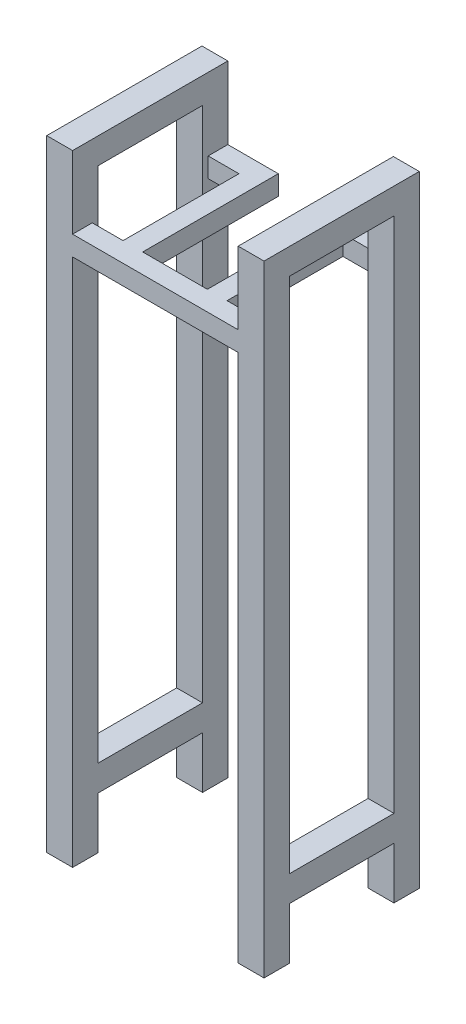
SolidWorks part; units mm, degrees
ref_plane "Front Plane" through (0, 0, 0) normal (0, 0, 1) x (1, 0, 0)
ref_plane "Top Plane" through (0, 0, 0) normal (0, 1, 0) x (1, 0, 0)
ref_plane "Right Plane" through (0, 0, 0) normal (1, 0, 0) x (0, 0, -1)
sketch "Sketch5" plane through (0, 0, 0) normal (0, 0, 1) x (1, 0, 0)
  line L0 (105, 600) -> (105, 0) construction
  line L1 (0, 0) -> (210, 0)
  line L2 (0, 0) -> (0, 600)
  line L3 (0, 600) -> (210, 600)
  line L4 (210, 0) -> (210, 600)
  line L6 (185, 575) -> (25, 575)
  line L7 (185, 575) -> (185, 0)
  line L8 (185, 0) -> (25, 0)
  line L9 (25, 575) -> (25, 0)
  line L10 (185, 575) -> (25, 0) construction
  line L11 (185, 0) -> (25, 575) construction
  point P7 (105, 287.5)
  dimension "D1" = 600
  dimension "D2" = 210
  dimension "D3" = 25
  dimension "D4" = 25
extrude "Boss-Extrude5" add sketch "Sketch5" along normal blind 150 contours L9 L6 L7 L1 L4 L3 L2
sketch "Sketch6" plane through (0, 0, 0) normal (-1, 0, 0) x (0, 0, 1)
  line L0 (75, 600) -> (75, 0) construction
  line L1 (150, 600) -> (0, 600) construction
  line L2 (150, 0) -> (0, 0) construction
  line L4 (125.5453, 50) -> (24.4547, 50)
  line L5 (125.5453, 50) -> (125.5453, 0)
  line L6 (125.5453, 0) -> (24.4547, 0)
  line L7 (24.4547, 50) -> (24.4547, 0)
  line L8 (125.5453, 50) -> (24.4547, 0) construction
  line L9 (125.5453, 0) -> (24.4547, 50) construction
  line L10 (125.5453, 75) -> (24.4547, 75)
  line L11 (125.5453, 75) -> (125.5453, 575)
  line L12 (125.5453, 575) -> (24.4547, 575)
  line L13 (24.4547, 75) -> (24.4547, 575)
  line L14 (125.5453, 75) -> (24.4547, 575) construction
  line L15 (125.5453, 575) -> (24.4547, 75) construction
  point P6 (75, 25)
  point P11 (75, 325)
  point P17 (0, 0)
  dimension "D1" = 25
  dimension "D3" = 25
  dimension "D4" = 50
extrude "Cut-Extrude1" cut sketch "Sketch6" against normal through all
sketch "Sketch7" plane through (0, 600, 0) normal (0, 1, 0) x (1, 0, 0)
  line L0 (105, -150) -> (105, 0) construction
  line L1 (0, -150) -> (210, -150) construction
  line L2 (0, 0) -> (210, 0) construction
  line L3 (210, -150) -> (210, 0) construction
  line L4 (25, -150) -> (185, -150)
  line L5 (25, -150) -> (25, 0)
  line L6 (25, 0) -> (185, 0)
  line L7 (185, -150) -> (185, 0)
  line L8 (25, -150) -> (185, 0) construction
  line L9 (25, 0) -> (185, -150) construction
  point P6 (105, -75)
  dimension "D1" = 0
  dimension "D2" = 25
extrude "Cut-Extrude2" cut sketch "Sketch7" against normal up to next
sketch "Sketch8" plane through (0, 0, 0) normal (0, 0, -1) x (-1, 0, 0)
  line L0 (-185, 600) -> (-185, 0) construction
  line L1 (-185, 530) -> (-25, 530)
  line L2 (-185, 530) -> (-185, 511)
  line L3 (-185, 511) -> (-25, 511)
  line L4 (-25, 530) -> (-25, 511)
  line L5 (-25, 600) -> (-25, 0) construction
  line L7 (-105, 530) -> (-105, 511) construction
  line L8 (0, 600) -> (-25, 600) construction
  line L9 (-73.75, 511) -> (-136.25, 511)
  line L10 (-73.75, 511) -> (-73.75, 530)
  line L11 (-73.75, 530) -> (-136.25, 530)
  line L12 (-136.25, 511) -> (-136.25, 530)
  line L13 (-73.75, 511) -> (-136.25, 530) construction
  line L14 (-73.75, 530) -> (-136.25, 511) construction
  point P12 (-105, 520.5)
  point P17 (-136.25, 520.5)
  point P18 (-12.5, 600)
  line M6 (-25, 600) -> (-25, 0)
  dimension "D1" = 19
  dimension "D2" = 70
  dimension "D3" = 62.5
extrude "Boss-Extrude6" add sketch "Sketch8" against normal blind 19 contours L3 L12 L1 L2 | L10 L3 L1 M6
sketch "Sketch10" plane through (0, 530, 0) normal (0, 1, 0) x (1, 0, 0)
  line L0 (136.25, 0) -> (73.75, 0) construction
  line L1 (105, 0) -> (105, -164.7108) construction
  line L2 (185, -150) -> (25, -150)
  line L3 (185, -150) -> (185, -131)
  line L4 (185, -150) -> (185, 0) construction
  line L5 (185, -131) -> (155.25, -131)
  line L6 (155.25, -131) -> (155.25, -19)
  line L7 (185, -19) -> (136.25, -19) construction
  line L8 (155.25, -19) -> (136.25, -19)
  line L9 (136.25, -19) -> (136.25, -131)
  line L10 (136.25, -131) -> (73.75, -131)
  line L11 (54.75, -19) -> (73.75, -19)
  line L12 (25, -150) -> (25, -131)
  line L13 (73.75, -19) -> (73.75, -131)
  line L14 (54.75, -131) -> (54.75, -19)
  line L15 (25, -131) -> (54.75, -131)
  point P25 (105, -131)
  point P26 (105, -150)
  dimension "D1" = 19
  dimension "D2" = 19
extrude "Boss-Extrude8" add sketch "Sketch10" against normal blind 19
